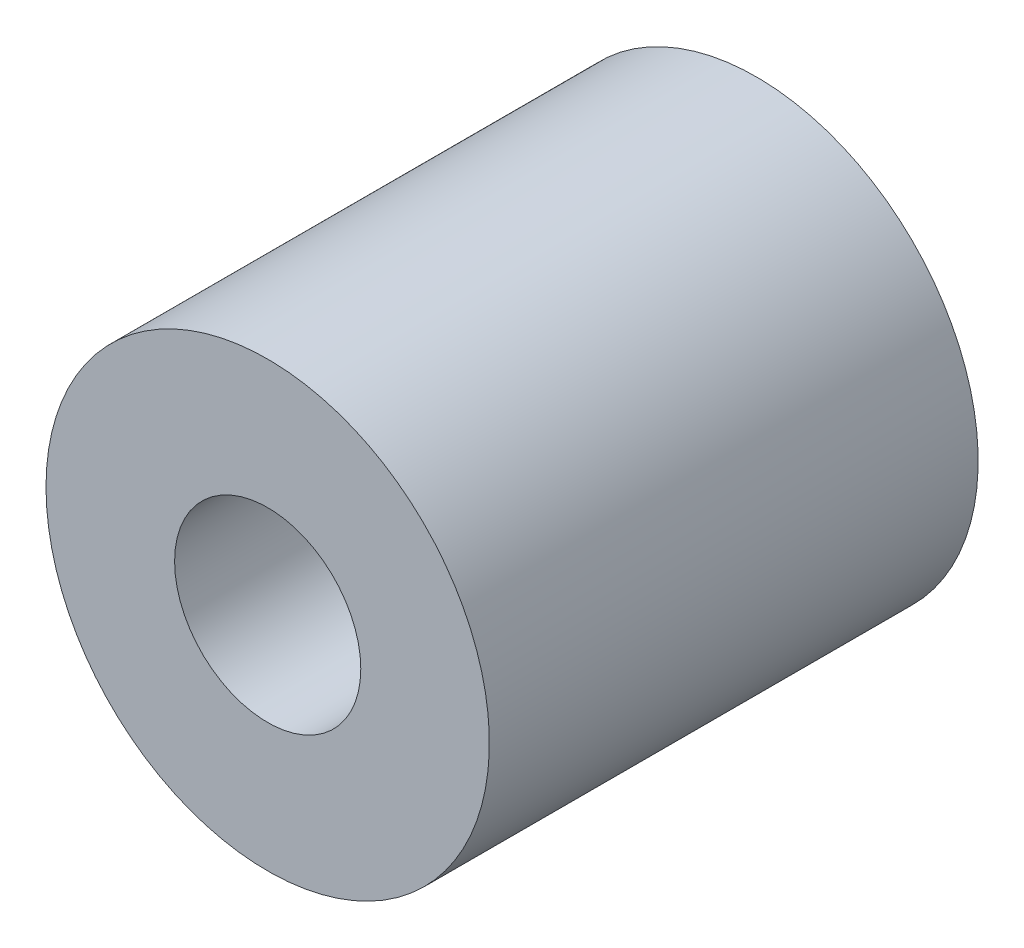
SolidWorks part; units mm, degrees
ref_plane "Front Plane" through (0, 0, 0) normal (0, 0, 1) x (1, 0, 0)
ref_plane "Top Plane" through (0, 0, 0) normal (0, 1, 0) x (1, 0, 0)
ref_plane "Right Plane" through (0, 0, 0) normal (1, 0, 0) x (0, 0, -1)
sketch "Sketch1" plane through (0, 0, 0) normal (0, 0, 1) x (1, 0, 0)
  circle A0 centre (0, 0) radius 9.525
  circle A1 centre (0, 0) radius 4
extrude "Boss-Extrude1" add sketch "Sketch1" along normal blind 21
